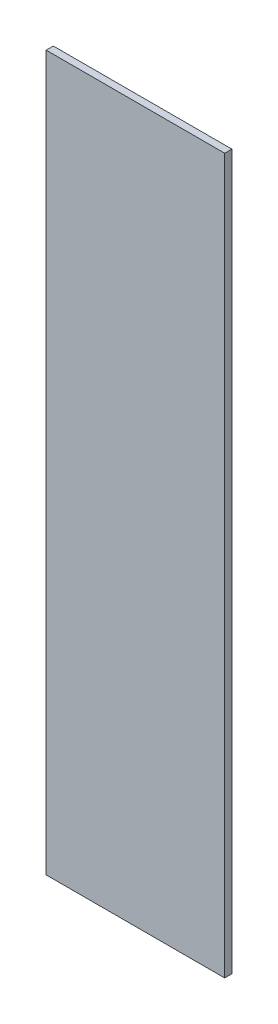
SolidWorks part; units mm, degrees
ref_plane "Front Plane" through (0, 0, 0) normal (0, 0, 1) x (1, 0, 0)
ref_plane "Top Plane" through (0, 0, 0) normal (0, 1, 0) x (1, 0, 0)
ref_plane "Right Plane" through (0, 0, 0) normal (1, 0, 0) x (0, 0, -1)
sketch "Sketch1" plane through (0, 0, 0) normal (0, 1, 0) x (1, 0, 0)
  line L1 (25, -1) -> (-25, -1)
  line L2 (25, -1) -> (25, 1)
  line L3 (25, 1) -> (-25, 1)
  line L4 (-25, -1) -> (-25, 1)
  line L5 (25, -1) -> (-25, 1) construction
  line L6 (25, 1) -> (-25, -1) construction
  point P0 (0, 0)
extrude "Boss-Extrude1" add sketch "Sketch1" along normal blind 200
